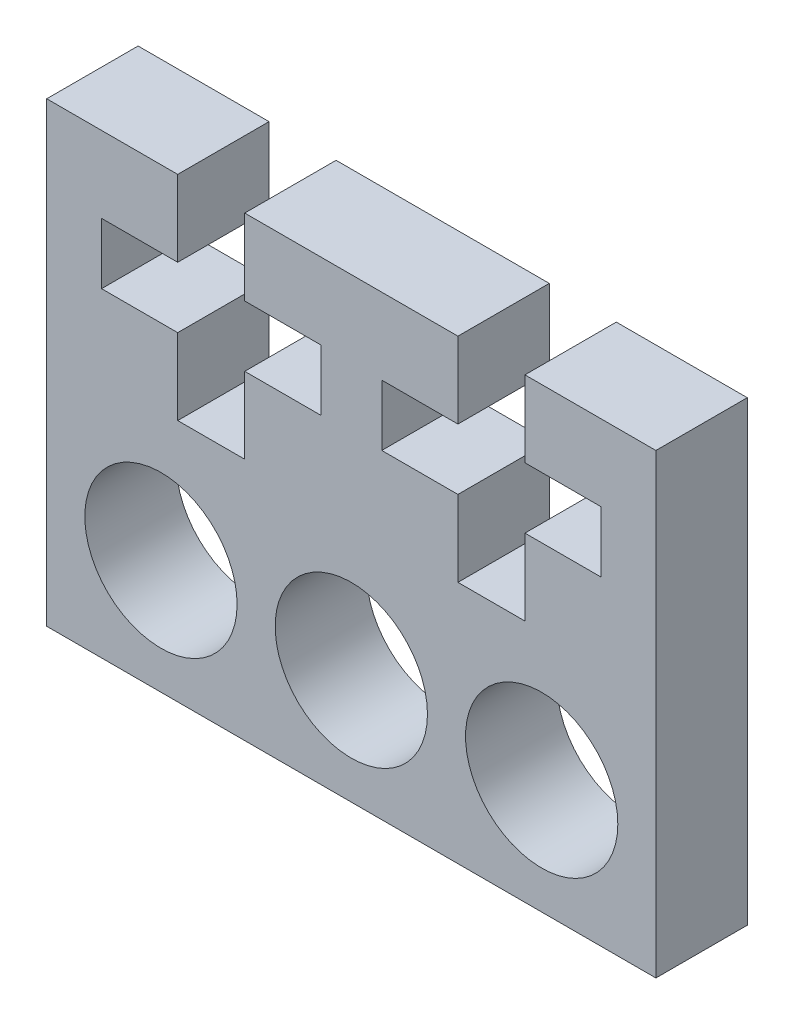
SolidWorks part; units mm, degrees
ref_plane "Front Plane" through (0, 0, 0) normal (0, 0, 1) x (1, 0, 0)
ref_plane "Top Plane" through (0, 0, 0) normal (0, 1, 0) x (1, 0, 0)
ref_plane "Right Plane" through (0, 0, 0) normal (1, 0, 0) x (0, 0, -1)
sketch "Sketch1" plane through (0, 0, 0) normal (0, 0, 1) x (1, 0, 0)
  line L0 (0, 7.5) -> (0, -7.5) construction
  line L1 (-10, -7.5) -> (10, -7.5)
  line L2 (-10, -7.5) -> (-10, 7.5)
  line L3 (-10, 7.5) -> (-5.7, 7.5)
  line L4 (10, -7.5) -> (10, 7.5)
  line L5 (-10, -7.5) -> (10, 7.5) construction
  line L6 (-10, 7.5) -> (10, -7.5) construction
  line L7 (-5.7, 7.5) -> (-5.7, 5)
  line L8 (-5.7, 5) -> (-8.2, 5)
  line L9 (-8.2, 5) -> (-8.2, 3)
  line L10 (-8.2, 3) -> (-5.7, 3)
  line L11 (-5.7, 3) -> (-5.7, 0.5)
  line L12 (-5.7, 0.5) -> (-3.5, 0.5)
  line L13 (-3.5, 0.5) -> (-3.5, 3)
  line L14 (-3.5, 3) -> (-1, 3)
  line L15 (-1, 3) -> (-1, 5)
  line L16 (-1, 5) -> (-3.5, 5)
  line L17 (-3.5, 5) -> (-3.5, 7.5)
  line L18 (3.5, 5) -> (3.5, 7.5)
  line L19 (1, 5) -> (3.5, 5)
  line L20 (1, 3) -> (1, 5)
  line L21 (3.5, 3) -> (1, 3)
  line L22 (3.5, 0.5) -> (3.5, 3)
  line L23 (5.7, 0.5) -> (3.5, 0.5)
  line L24 (5.7, 3) -> (5.7, 0.5)
  line L25 (8.2, 3) -> (5.7, 3)
  line L26 (8.2, 5) -> (8.2, 3)
  line L27 (5.7, 5) -> (8.2, 5)
  line L28 (5.7, 7.5) -> (5.7, 5)
  line L29 (-3.5, 7.5) -> (3.5, 7.5)
  line L30 (5.7, 7.5) -> (10, 7.5)
  circle A0 centre (0, -3.75) radius 2.5
  circle A1 centre (-6.25, -3.75) radius 2.5
  circle A2 centre (6.25, -3.75) radius 2.5
  point P0 (0, 0)
  dimension "D7" = 5
  dimension "D1" = 15
  dimension "D2" = 2.5
  dimension "D3" = 2
  dimension "D4" = 2.5
  dimension "D5" = 1.8
  dimension "D6" = 2.5
  dimension "D8" = 20
  dimension "D9" = 3.75
  dimension "D10" = 6.25
  dimension "D11" = 6.25
  dimension "D12" = 2.2
extrude "Boss-Extrude1" add sketch "Sketch1" along normal blind 3
